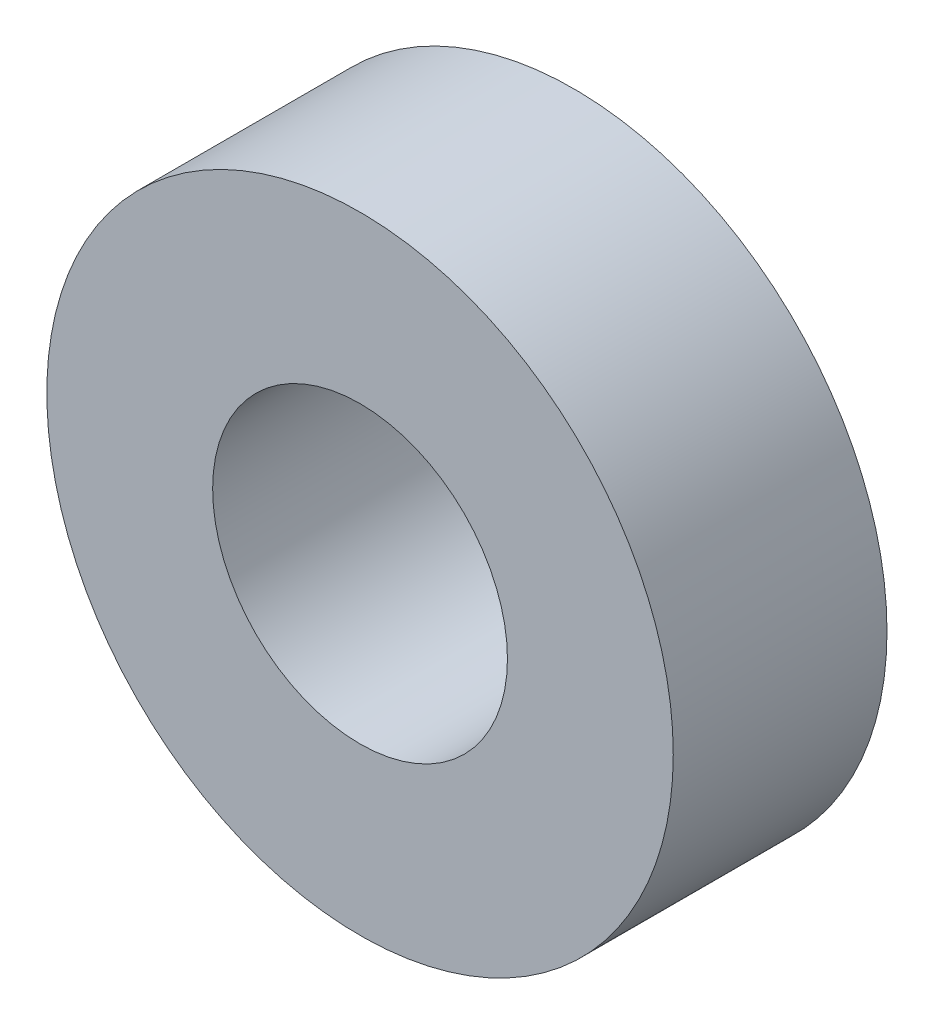
SolidWorks part; units mm, degrees
ref_plane "Front Plane" through (0, 0, 0) normal (0, 0, 1) x (1, 0, 0)
ref_plane "Top Plane" through (0, 0, 0) normal (0, 1, 0) x (1, 0, 0)
ref_plane "Right Plane" through (0, 0, 0) normal (1, 0, 0) x (0, 0, -1)
sketch "Sketch1" plane through (0, 0, 0) normal (0, 0, 1) x (1, 0, 0)
  circle A0 centre (0, 0) radius 8.5
  circle A1 centre (0, 0) radius 4
  dimension "D1" = 17
  dimension "D2" = 8
extrude "Boss-Extrude1" add sketch "Sketch1" along normal blind 5.8
